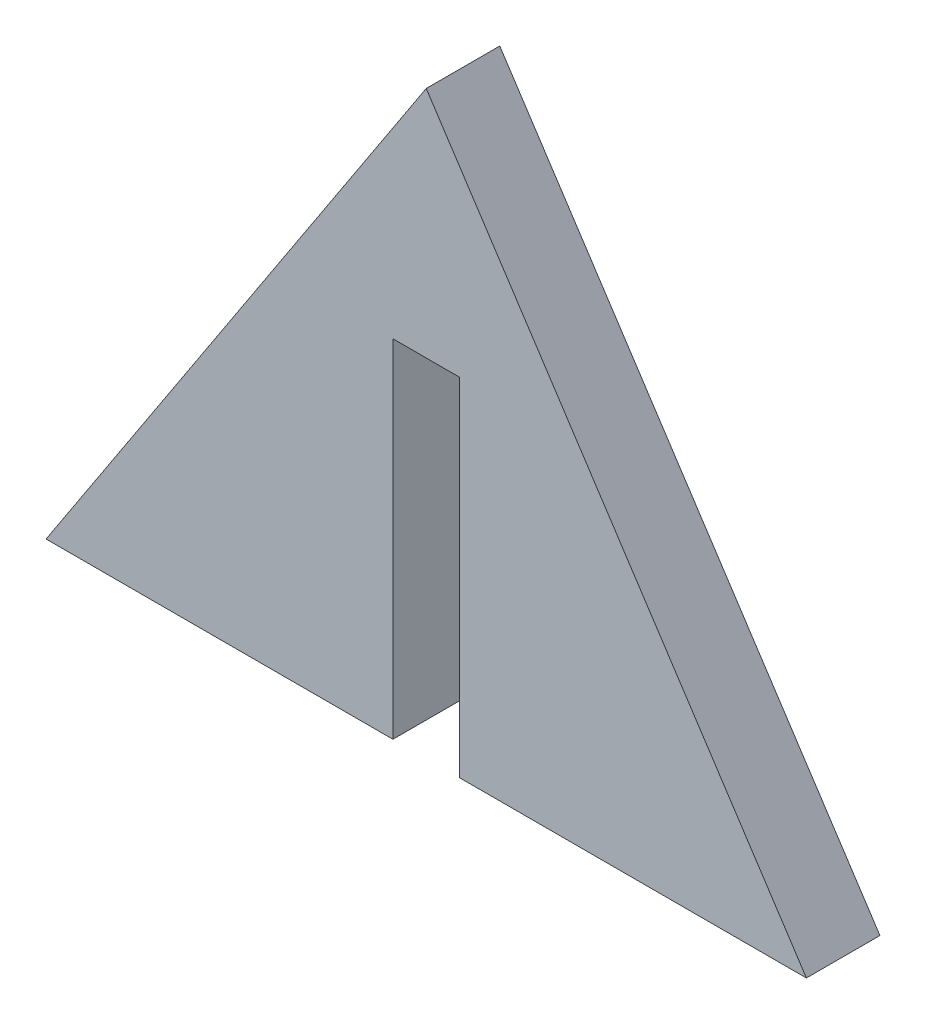
SolidWorks part; units mm, degrees
ref_plane "Front Plane" through (0, 0, 0) normal (0, 0, 1) x (1, 0, 0)
ref_plane "Top Plane" through (0, 0, 0) normal (0, 1, 0) x (1, 0, 0)
ref_plane "Right Plane" through (0, 0, 0) normal (1, 0, 0) x (0, 0, -1)
sketch "Sketch1" plane through (0, 0, 0) normal (0, 0, 1) x (1, 0, 0)
  line L0 (-13.9192, 6.4395) -> (0, 27.6861)
  line L1 (0, 27.6861) -> (13.9192, 6.4395)
  line L2 (13.9192, 6.4395) -> (1.2192, 6.4395)
  line L3 (-1.2192, 6.4395) -> (-1.2192, 19.1395)
  line L4 (-1.2192, 19.1395) -> (1.2192, 19.1395)
  line L5 (1.2192, 19.1395) -> (1.2192, 6.4395)
  line L7 (-1.2192, 6.4395) -> (-13.9192, 6.4395)
  point P2 (0, 19.1395)
  dimension "D1" = 25.4
  dimension "D2" = 2.4384
  dimension "D4" = 12.7
  dimension "D5" = 12.7
extrude "Boss-Extrude1" add sketch "Sketch1" along normal blind 2.6924
equation "\"T\"= 0.106"
equation "\"D2@Sketch1\"=\"T\" - 0.010"
equation "\"D1@Boss-Extrude1\"=\"T\""
